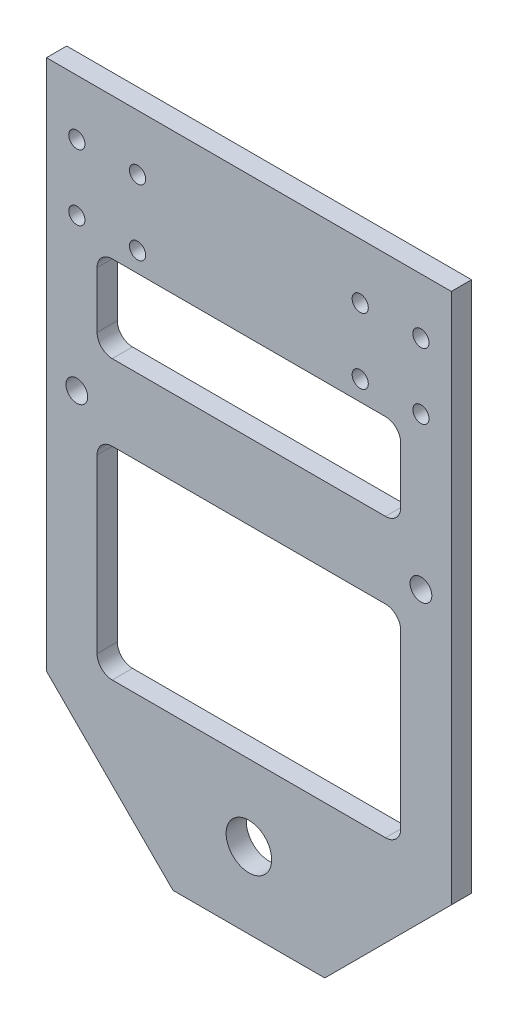
SolidWorks part; units mm, degrees
ref_plane "前视基准面" through (0, 0, 0) normal (0, 0, 1) x (1, 0, 0)
ref_plane "上视基准面" through (0, 0, 0) normal (0, 1, 0) x (1, 0, 0)
ref_plane "右视基准面" through (0, 0, 0) normal (1, 0, 0) x (0, 0, -1)
sketch "草图1" plane through (0, 0, 0) normal (0, 0, 1) x (1, 0, 0)
  line L0 (0, -44) -> (0, 86) construction
  line L1 (-40, 86) -> (40, 86)
  line L2 (-40, 86) -> (-40, -44)
  line L3 (-40, -44) -> (40, -44)
  line L4 (40, 86) -> (40, -44)
  circle A0 centre (0, -29) radius 4.5
  dimension "D1" = 9
  dimension "D4" = 130
  dimension "D5" = 15
  dimension "D2" = 80
extrude "凸台-拉伸1" add sketch "草图1" against normal blind 4
chamfer "倒角1" distance 25 angle 45 2 edges at (-40, -44, -2) (40, -44, -2)
sketch "草图3" plane through (0, 0, -4) normal (0, 0, -1) x (-1, 0, 0)
  line L2 (-30, 74.4134) -> (-30, 44)
  line L3 (-27, 41) -> (27, 41)
  line L4 (30, 74.4134) -> (30, 44)
  line L5 (-27, 26) -> (27, 26)
  line L6 (-30, 23) -> (-30, -11)
  line L7 (-27, -14) -> (27, -14)
  line L8 (30, 23) -> (30, -11)
  line L9 (-40, -19) -> (-40, 86) construction
  line L10 (40, 86) -> (40, -19) construction
  line L21 (-17.6067, 58.07) -> (27, 58.07)
  line L23 (-27, 58.07) -> (-17.6067, 58.07)
  line L25 (-30, 74.4134) -> (-30, 55.07)
  line L27 (30, 74.4134) -> (30, 55.07)
  arc A0 (27, 26) -> (30, 23) centre (27, 23) cw
  arc A1 (27, -14) -> (30, -11) centre (27, -11) ccw
  arc A2 (-30, -11) -> (-27, -14) centre (-27, -11) ccw
  arc A3 (-27, 26) -> (-30, 23) centre (-27, 23) ccw
  arc A4 (-30, 44) -> (-27, 41) centre (-27, 44) ccw
  arc A5 (27, 41) -> (30, 44) centre (27, 44) ccw
  arc A14 (30, 55.07) -> (27, 58.07) centre (27, 55.07) ccw
  arc A19 (-30, 55.07) -> (-27, 58.07) centre (-27, 55.07) cw
  point P8 (0, 0)
  point P16 (30, 26)
  point P19 (30, -14)
  point P28 (30, 41)
  point P31 (-10, 71)
  dimension "D9" = 3
  dimension "D10" = 3
  dimension "D2" = 10
  dimension "D3" = 10
  dimension "D4" = 15
  dimension "D5" = 10
  dimension "D6" = 10
  dimension "D7" = 50
  dimension "D8" = 40
extrude "切除-拉伸1" cut sketch "草图3" against normal blind 5
sketch "草图4" plane through (0, 0, -4) normal (0, 0, -1) x (-1, 0, 0)
  line L0 (-40, -19) -> (-40, 86) construction
  line L1 (40, 86) -> (40, -19) construction
  line L2 (-27, 41) -> (27, 41) construction
  circle A0 centre (-34, 32) radius 2.15
  circle A1 centre (34, 32) radius 2.15
  dimension "D1" = 4.3
  dimension "D2" = 6
  dimension "D3" = 6
  dimension "D4" = 9
  dimension "D5" = 9
extrude "切除-拉伸2" cut sketch "草图4" against normal blind 4
sketch "草图5" plane through (0, 0, -4) normal (0, 0, -1) x (-1, 0, 0)
  circle A0 centre (34, 75) radius 1.6
  circle A1 centre (22, 75) radius 1.6
  circle A2 centre (-22, 75) radius 1.6
  circle A3 centre (-34, 75) radius 1.6
  circle A4 centre (34, 62) radius 1.6
  circle A5 centre (22, 62) radius 1.6
  circle A6 centre (-22, 62) radius 1.6
  circle A7 centre (-34, 62) radius 1.6
  point P8 (-34, 79.6751)
  point P9 (0, 0)
  point P10 (-34, 79)
  point P12 (-22, 79)
  point P14 (22, 79)
  point P16 (34, 79)
  point P26 (-34, 62)
  point P28 (-22, 62)
  point P30 (21.7717, 62.1159)
  point P32 (34, 62)
  point P34 (21.7717, 62.1159)
  point P35 (22, 62)
  point P37 (34, 75)
  point P39 (22, 75)
  point P41 (-22, 75)
  point P43 (-34, 75)
extrude "切除-拉伸3" cut sketch "草图5" against normal blind 4
